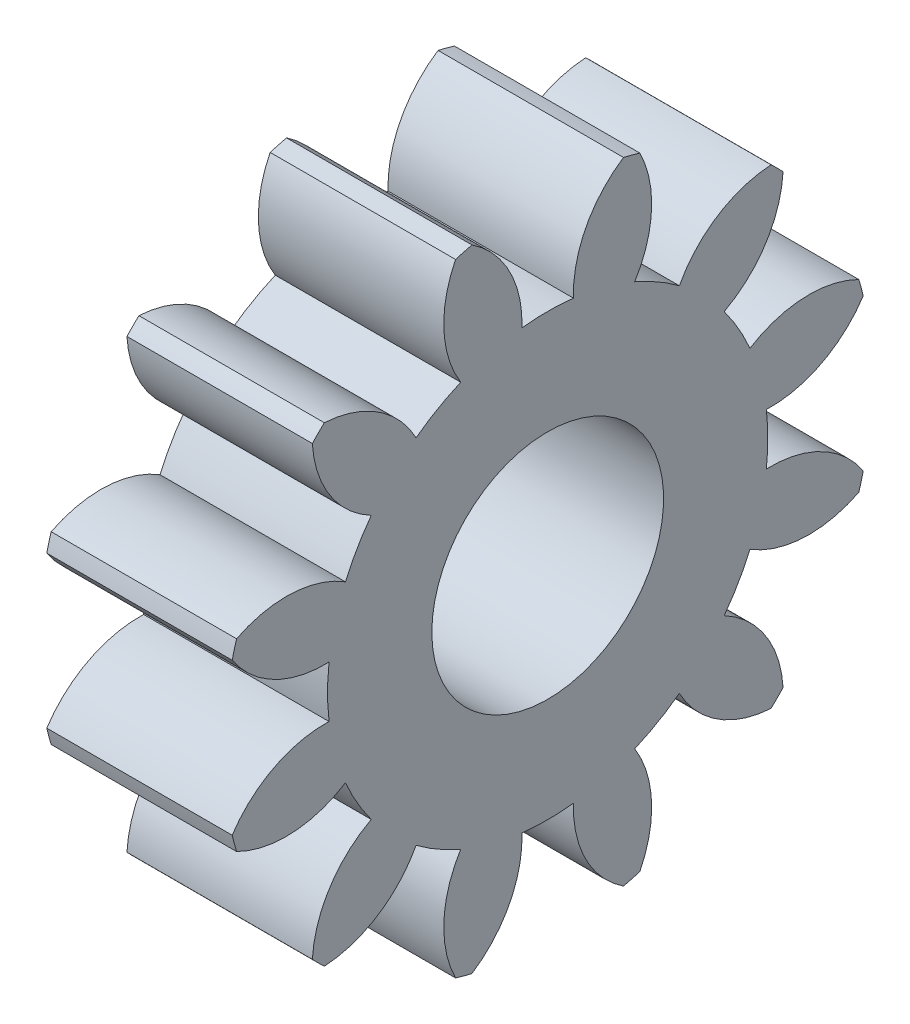
SolidWorks part; units mm, degrees
ref_plane "Plane1" through (0, 0, 0) normal (0, 0, 1) x (1, 0, 0)
ref_plane "Plane2" through (0, 0, 0) normal (0, 1, 0) x (1, 0, 0)
ref_plane "Plane3" through (0, 0, 0) normal (1, 0, 0) x (0, 0, -1)
sketch "HoldingSke" plane through (0, 0, 0) normal (0, 1, 0) x (1, 0, 0)
  line L0 (0, 0) -> (0.4891, -0.104)
  line L1 (-15, 0) -> (100, 0) construction
  line L2 (0, 0) -> (-2.1039, 2.3779)
  line L3 (0, 0) -> (-11.863, 4.5341)
  line L4 (0, 0) -> (8.4473, 1.7955)
  line L5 (0, 0) -> (-46.8476, -17.4728)
  line L6 (0, 0) -> (-6.6317, -4.4744)
  line L7 (-2.1039, 2.3779) -> (8.6586, 51.2059)
  line L8 (-76.2, 54.61) -> (-74.4, 54.61)
  line L9 (-71.009, 38.7566) -> (-53.1078, 45.2721)
  line L10 (-76.2, 71.12) -> (104.1128, 71.12)
  line L11 (0, 0) -> (-8, 0)
  line L12 (-76.2, 101.6) -> (-76.133, 101.6)
  line L13 (24.9733, 27.94) -> (52.9518, 28.4284)
  line L14 (24.9733, 27.94) -> (24.9743, 27.94)
  line L15 (24.9733, 27.94) -> (100.4006, 29.5858)
  line L16 (-63.627, -2) -> (-12.827, -2)
  circle A0 centre (0, 0) radius 5
  circle A1 centre (0, 0) radius 9.499
  circle A2 centre (0, 0) radius 37.5
  circle A3 centre (0, 0) radius 5
  dimension "MHD" = 18.998
  dimension "Hub_dia" = 75
  dimension "Bore" = 10
  dimension "MBD" = 10
  dimension "Num_teeth" = 12
  dimension "Pitch" = 0.5
  dimension "Overall_len" = 50
  dimension "Show_teeth" = 12
  dimension "Thickness" = 8
  dimension "OAL" = 50.0001
  dimension "T_dim" = 1.8
  dimension "Ap" = 20
  dimension "H" = 19.05
  dimension "Pitch_radius" = 180.3128
  dimension "Width" = 8
  dimension "Backlash" = 0.067
  dimension "Addendum_fac" = 1
  dimension "Dedendum_fac" = 1.25
  dimension "Clearance_fac" = 0.25
  dimension "Dedendum_add" = 0.001
  dimension "Module" = 2
sketch "BasProSke" plane through (0, 0, 0) normal (0, 1, 0) x (1, 0, 0)
  line L0 (-10, 0) -> (60, 0) construction
  line L1 (0, 0) -> (0, 14)
  line L2 (0, 0) -> (8, 0)
  line L3 (8, 0) -> (8, 14)
  line L4 (8, 14) -> (0, 14)
  dimension "Thickness" = 8
  dimension "Diameter" = 28
revolve "Base-Revolve" add sketch "BasProSke" angle 360 about L0
sketch "TooCutSke" plane through (0, 0, 0) normal (1, 0, 0) x (0, 0, -1)
  line L1 (0, 0) -> (0, 107) construction
  line L2 (0, 0) -> (-1.6834, 11.8813) construction
  line L3 (0, 0) -> (-6.1662, 23.0126) construction
  line L4 (-1.6834, 11.8813) -> (-3.0831, 11.5063) construction
  arc A0 (1.1119, 9.4337) -> (-1.1119, 9.4337) centre (0, 0) ccw
  arc A1 (3.2981, 13.6321) -> (-3.2981, 13.6321) centre (0, 0) ccw
  circle A2 centre (0, 0) radius 12 construction
  circle A3 centre (0, 0) radius 11.2763 construction
  arc A4 (-1.1119, 9.4337) -> (-3.2981, 13.6321) centre (-5.9089, 9.6042) ccw
  arc A5 (3.2981, 13.6321) -> (1.1119, 9.4337) centre (5.9089, 9.6042) ccw
  dimension "Root_dia" = 18.998
  dimension "Overcut_dia" = 28.0508
  dimension "Pitch_dia" = 24
  dimension "Base_dia" = 22.5526
  dimension "Flank_rad" = 4.8
  dimension "Half_ang" = 15
  dimension "Half_CT" = 1.4491
extrude "ToothCut" cut sketch "TooCutSke" along normal through all
fillet "Breaks" [suppressed] radius 0.04
fillet "RootFillets" [suppressed] radius 0.501
pattern_circular "TeethCuts" count 12 every 30 about axis through (-10, 0, 0) along (1, 0, 0) of "ToothCut", "RootFillets", "Breaks"
sketch "HubNeaOneSke" plane through (0, 0, 0) normal (-1, 0, 0) x (0, 0, 1)
  circle A0 centre (0, 0) radius 9.499
  dimension "Diameter" = 18.998
extrude "HubNearOne" [suppressed] add sketch "HubNeaOneSke" along normal blind 42.0001
sketch "HubNeaBotSke" plane through (0, 0, 0) normal (-1, 0, 0) x (0, 0, 1)
  circle A0 centre (0, 0) radius 9.499
  dimension "Diameter" = 18.998
extrude "HubNearBoth" [suppressed] add sketch "HubNeaBotSke" along normal blind 21
ref_plane "FarPln" through (8, 0, 0) normal (1, 0, 0) x (0, 0, -1)
sketch "HubFarSke" plane through (8, 0, 0) normal (1, 0, 0) x (0, 0, -1)
  circle A0 centre (0, 0) radius 9.499
  dimension "Diameter" = 18.998
extrude "HubFar" [suppressed] add sketch "HubFarSke" along normal blind 21
sketch "BorSke" plane through (0, 0, 0) normal (1, 0, 0) x (0, 0, -1)
  circle A0 centre (0, 0) radius 5
  dimension "Diameter" = 10
extrude "Bore" cut sketch "BorSke" along normal mid plane 100.0001
sketch "KeySke" plane through (0, 0, 0) normal (1, 0, 0) x (0, 0, -1)
  line L0 (-2, 0) -> (-2, 6.8)
  line L1 (-2, 6.8) -> (2, 6.8)
  line L2 (2, 6.8) -> (2, 0)
  line L3 (0, 0) -> (0, 34) construction
  line L4 (-2, 0) -> (2, 0)
  dimension "Offset" = 6.8
  dimension "Width" = 4
extrude "Keyway" [suppressed] cut sketch "KeySke" along normal mid plane 100.0001
pattern_circular "Keyway2" [suppressed] count 2 every 90 about axis through (-10, 0, 0) along (1, 0, 0)
equation "' \"Module@HoldingSke\" = 6.35"
equation "' \"Num_teeth@HoldingSke\" = 12"
equation "' \"Ap@HoldingSke\" =  20"
equation "' \"Ap@HoldingSke\" = 20"
equation "' \"Width@HoldingSke\" = 0.5 * 25.4"
equation "' \"Hub_dia@HoldingSke\"= 1 * 25.4"
equation "' \"Hub_dia@HoldingSke\" = 1 * 25.4"
equation "' \"Overall_len@HoldingSke\" = 1.0 * 25.4"
equation "' \"Bore@HoldingSke\" = 0.75 * 25.4"
equation "' \"T_dim@HoldingSke\" = 0.1 * 25.4"
equation "' \"Width@KeySke\" = 0.25 * 25.4"
equation "' \"Show_teeth@HoldingSke\" = 13"
equation "' \"Backlash@HoldingSke\" = 0.009 * 25.4"
equation "' \"Addendum_fac@HoldingSke\" = 1.0"
equation "' \"Dedendum_fac@HoldingSke\" = 1.25"
equation "' \"Dedendum_add@HoldingSke\" = 0.00005 * 25.4"
equation "' \"Clearance_fac@HoldingSke\" = 0.25"
equation "\"Pitch@HoldingSke\" = 1 / \"Module@HoldingSke\""
equation "\"Overcut_dia@TooCutSke\" = (\"Num_teeth@HoldingSke\" + 2 * \"Addendum_fac@HoldingSke\") / \"Pitch@HoldingSke\" + 0.002 * 25.4"
equation "\"Pitch_dia@TooCutSke\" = \"Num_teeth@HoldingSke\" / \"Pitch@HoldingSke\""
equation "\"Base_dia@TooCutSke\" = \"Num_teeth@HoldingSke\" / \"Pitch@HoldingSke\" * cos((\"Ap@HoldingSke\"  * 3.14159265 / 180))"
equation "\"Root_dia@TooCutSke\" = (\"Num_teeth@HoldingSke\" + 2) / \"Pitch@HoldingSke\" - 2 * (\"Addendum_fac@HoldingSke\" + \"Dedendum_fac@HoldingSke\") / \"Pitch@HoldingSke\" - \"Dedendum_add@HoldingSke\" * 2"
equation "\"Half_ang@TooCutSke\" = 180 / \"Num_teeth@HoldingSke\""
equation "\"Half_CT@TooCutSke\" = \"Num_teeth@HoldingSke\" / \"Pitch@HoldingSke\" * sin((3.14159265 / 2 / \"Num_teeth@HoldingSke\")) / 2 - 7 * \"Backlash@HoldingSke\" / 4"
equation "\"Flank_rad@TooCutSke\" = \"Num_teeth@HoldingSke\" / \"Pitch@HoldingSke\" / 5"
equation "\"Radius@RootFillets\" = \"Clearance_fac@HoldingSke\" / \"Pitch@HoldingSke\" + \"Dedendum_add@HoldingSke\""
equation "\"Break_rad@Breaks\" = 0.02 / \"Pitch@HoldingSke\""
equation "\"Thickness@HoldingSke\" = \"Width@HoldingSke\""
equation "\"OAL@HoldingSke\" = \"Thickness@HoldingSke\""
equation "\"MHD@HoldingSke\" = (\"Num_teeth@HoldingSke\" + 2) / \"Pitch@HoldingSke\" - 2 * (\"Addendum_fac@HoldingSke\" + \"Dedendum_fac@HoldingSke\")  / \"Pitch@HoldingSke\" - \"Dedendum_add@HoldingSke\" * 2"
equation "\"MBD@HoldingSke\" = (\"Num_teeth@HoldingSke\" + 2) / \"Pitch@HoldingSke\" - 2 * (\"Addendum_fac@HoldingSke\" + \"Dedendum_fac@HoldingSke\")  / \"Pitch@HoldingSke\" - \"Dedendum_add@HoldingSke\" * 2 - 0.002 * 25.4"
equation "\"MHD@HoldingSke\" = ((sgn( \"MHD@HoldingSke\" - \"Hub_dia@HoldingSke\" )-1)*( \"MHD@HoldingSke\" - \"Hub_dia@HoldingSke\" ))/-2+ \"Hub_dia@HoldingSke\""
equation "\"MBD@HoldingSke\" = ((sgn( \"MBD@HoldingSke\" - \"Bore@HoldingSke\" )-1)*( \"MBD@HoldingSke\" - \"Bore@HoldingSke\" ))/-2+ \"Bore@HoldingSke\""
equation "\"OAL@HoldingSke\" = ((sgn( \"OAL@HoldingSke\" - \"Overall_len@HoldingSke\" )+1)*( \"OAL@HoldingSke\" - \"Overall_len@HoldingSke\" ))/2 + \"Overall_len@HoldingSke\" + 0.000002 * 25.4"
equation "\"Num_teeth@TeethCuts\" = int( \"Show_teeth@HoldingSke\" ) + 1"
equation "\"Num_teeth@TeethCuts\" = ((sgn( \"Num_teeth@TeethCuts\" - \"Num_teeth@HoldingSke\" )-1)*( \"Num_teeth@TeethCuts\" - \"Num_teeth@HoldingSke\" ))/-2+ \"Num_teeth@HoldingSke\""
equation "\"Num_teeth@TeethCuts\" = ((sgn( \"Num_teeth@TeethCuts\" - 2.0)+1)*( \"Num_teeth@TeethCuts\" - 2.0))/2 +2.0"
equation "\"Angle@TeethCuts\" = 360.0 / \"Num_teeth@HoldingSke\""
equation "\"Diameter@BasProSke\" = (\"Num_teeth@HoldingSke\" + 2 * \"Addendum_fac@HoldingSke\") / \"Pitch@HoldingSke\""
equation "\"Thickness@BasProSke\"  = \"Thickness@HoldingSke\""
equation "' \"Fillet_rad@BasProSke\" =  \"Thickness@HoldingSke\" * 0.05"
equation "' \"Fillet_rad@BasProSke\" = \"Thickness@HoldingSke\" * 0.05"
equation "\"MHD@HoldingSke\" = ((sgn( \"MHD@HoldingSke\" - \"Root_dia@TooCutSke\" )-1)*( \"MHD@HoldingSke\" - \"Root_dia@TooCutSke\" ))/-2+ \"Root_dia@TooCutSke\""
equation "\"Diameter@HubNeaOneSke\" = \"MHD@HoldingSke\""
equation "\"Length@HubNearOne\" = \"OAL@HoldingSke\" - \"Thickness@BasProSke\""
equation "\"Diameter@HubNeaBotSke\" = \"MHD@HoldingSke\""
equation "\"Length@HubNearBoth\" = ( \"OAL@HoldingSke\" - \"Thickness@BasProSke\" ) / 2.0"
equation "\"Thickness@FarPln\" = \"Thickness@BasProSke\""
equation "\"Diameter@HubFarSke\" = \"MHD@HoldingSke\""
equation "\"Length@HubFar\" = ( \"OAL@HoldingSke\" - \"Thickness@BasProSke\" ) / 2.0"
equation "\"Diameter@BorSke\" = \"MBD@HoldingSke\""
equation "\"D1@Bore\" = \"OAL@HoldingSke\" * 2.0"
equation "\"D1@Keyway\" = \"OAL@HoldingSke\" * 2.0"
equation "\"Offset@KeySke\" = \"T_dim@HoldingSke\" + \"MBD@HoldingSke\" / 2.0"
